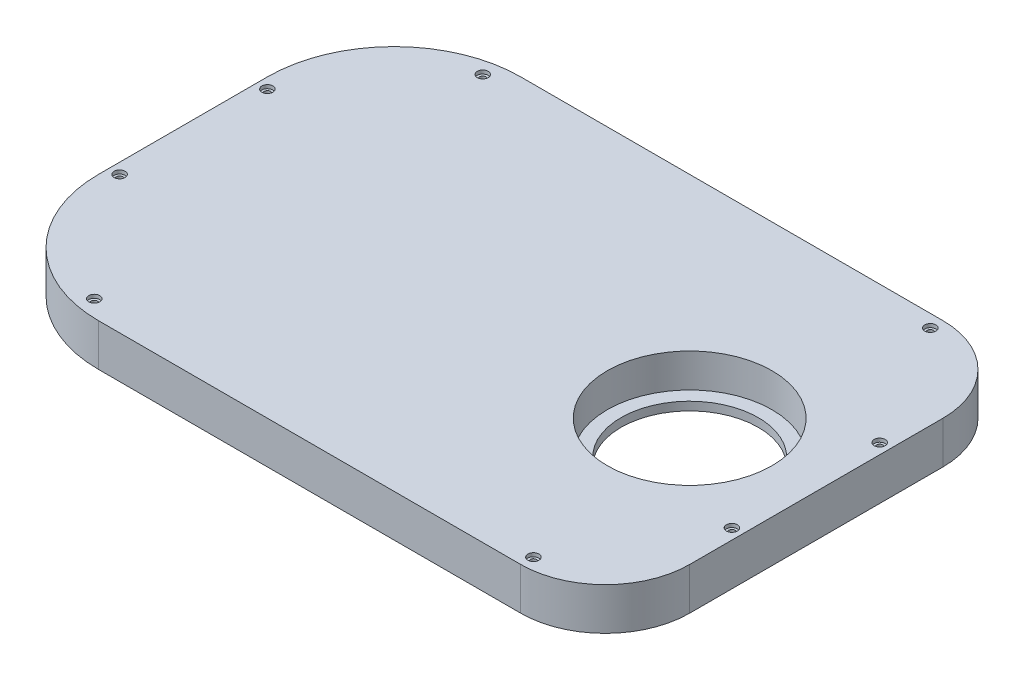
SolidWorks part; units mm, degrees
ref_plane "Front Plane" through (0, 0, 0) normal (0, 0, 1) x (1, 0, 0)
ref_plane "Top Plane" through (0, 0, 0) normal (0, 1, 0) x (1, 0, 0)
ref_plane "Right Plane" through (0, 0, 0) normal (1, 0, 0) x (0, 0, -1)
sketch "Sketch2" plane through (0, 0, 0) normal (0, 1, 0) x (1, 0, 0)
  line L1 (150, 100) -> (-150, 100)
  line L2 (150, 100) -> (150, -100)
  line L3 (150, -100) -> (-150, -100)
  line L4 (-150, 100) -> (-150, -100)
  line L5 (150, 100) -> (-150, -100) construction
  line L6 (150, -100) -> (-150, 100) construction
  point P0 (0, 0)
  dimension "D1" = 300
  dimension "D2" = 200
extrude "Boss-Extrude1" add sketch "Sketch2" along normal blind 20
sketch "Sketch3" plane through (0, 0, 0) normal (0, -1, 0) x (1, 0, 0)
  line L1 (140, 90) -> (-140, 90)
  line L2 (140, 90) -> (140, -90)
  line L3 (140, -90) -> (-140, -90)
  line L4 (-140, 90) -> (-140, -90)
  line L5 (140, 90) -> (-140, -90) construction
  line L6 (140, -90) -> (-140, 90) construction
  line L7 (135, 85) -> (-135, 85)
  line L8 (135, 85) -> (135, -85)
  line L9 (135, -85) -> (-135, -85)
  line L10 (-135, 85) -> (-135, -85)
  line L11 (135, 85) -> (-135, -85) construction
  line L12 (135, -85) -> (-135, 85) construction
  point P0 (0, 0)
  point P5 (0, 0)
  dimension "D1" = 280
  dimension "D2" = 180
  dimension "D3" = 270
  dimension "D4" = 170
extrude "Boss-Extrude2" add sketch "Sketch3" along normal blind 10
fillet "Fillet1" radius 40 6 edges at (135, -5, 85) (135, -5, -85) (140, -5, -90) (140, -5, 90) (150, 10, 100) (150, 10, -100)
fillet "Fillet2" radius 60 6 edges at (-135, -5, -85) (-135, -5, 85) (-140, -5, 90) (-150, 10, 100) (-140, -5, -90) (-150, 10, -100)
sketch "Sketch4" plane through (0, 20, 0) normal (0, 1, 0) x (1, 0, 0)
  circle A0 centre (90, 0) radius 39
  dimension "D1" = 78
extrude "Cut-Extrude1" cut sketch "Sketch4" against normal blind 16
sketch "Sketch5" plane through (0, 4, 0) normal (0, 1, 0) x (1, 0, 0)
  circle A0 centre (90, 0) radius 32.5
  dimension "D1" = 65
extrude "Cut-Extrude2" cut sketch "Sketch5" against normal blind 16
sketch "Sketch8" plane through (0, 0, 0) normal (0, -1, 0) x (1, 0, 0)
  circle A0 centre (90, 0) radius 32.5 construction
  circle A1 centre (-100, 92) radius 1.5
  circle A2 centre (-100, -92) radius 1.5
  circle A3 centre (-145, 35) radius 1.5
  circle A4 centre (-145, -35) radius 1.5
  circle A5 centre (110, 94) radius 1.5
  circle A6 centre (110, -94) radius 1.5
  circle A7 centre (145, 35) radius 1.5
  circle A8 centre (145, -35) radius 1.5
  point P0 (-70, 0)
  dimension "D2" = 3
  dimension "D3" = 3
  dimension "D4" = 3
  dimension "D5" = 3
  dimension "D6" = 3
  dimension "D7" = 3
  dimension "D8" = 3
  dimension "D9" = 3
  dimension "D1" = 160
  dimension "D10" = 30
  dimension "D11" = 30
  dimension "D12" = 92
  dimension "D13" = 92
  dimension "D14" = 94
  dimension "D15" = 94
  dimension "D16" = 180
  dimension "D17" = 180
  dimension "D18" = 35
  dimension "D19" = 35
  dimension "D20" = 35
  dimension "D21" = 35
  dimension "D22" = 215
  dimension "D23" = 215
  dimension "D24" = 75
  dimension "D25" = 75
extrude "Cut-Extrude3" cut sketch "Sketch8" against normal up to surface (20 mm away) up to face at (90, 20, 39)
sketch "Sketch9" plane through (0, 20, 0) normal (0, 1, 0) x (1, 0, 0)
  point P0 (110, 94)
  point P3 (145, 35)
  point P6 (145, -35)
  point P9 (110, -94)
  point P12 (-100, -92)
  point P15 (-145, -35)
  point P18 (-145, 35)
  point P21 (-100, 92)
hole_wizard "CBORE for M5 Hex Head Bolt1" positions "Sketch9" profile "Sketch10" counterbore size "M5" standard "ISO"
sketch "Sketch10" plane through (110, 20, -94) normal (1, 0, 0) x (0, 0, 1)
  line L0 (0, 0) -> (0, 20.9013)
  line L1 (0, 20.9013) -> (1.5, 20)
  line L2 (1.5, 20) -> (1.5, 1.7)
  line L3 (1.5, 1.7) -> (2.6, 1.7)
  line L4 (2.6, 1.7) -> (2.6, 0)
  line L5 (2.6, 0) -> (0, 0)
  line L10 (0, 20.9013) -> (-1.5, 20) construction
  line L11 (0, -6.35) -> (0, 107.95) construction
  dimension "Hole Dia." = 3
  dimension "Hole Depth" = 20
  dimension "C'Bore Dia." = 5.2
  dimension "C'Bore Depth" = 1.7
  dimension "Drill Angle" = 118
